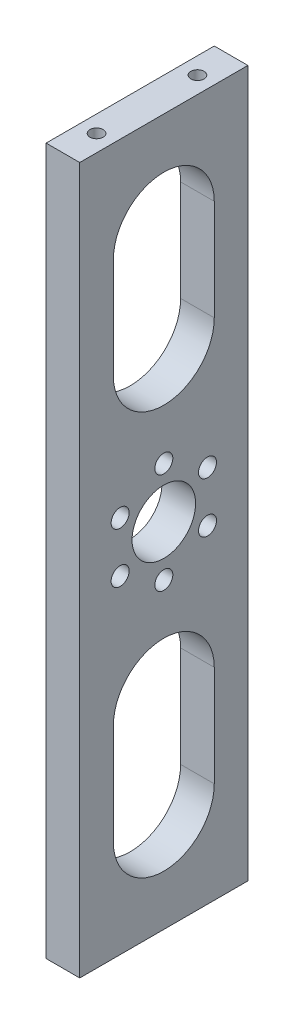
SolidWorks part; units mm, degrees
material "6061 Alloy"
ref_plane "Front Plane" through (0, 0, 0) normal (0, 0, 1) x (1, 0, 0)
ref_plane "Top Plane" through (0, 0, 0) normal (0, 1, 0) x (1, 0, 0)
ref_plane "Right Plane" through (0, 0, 0) normal (1, 0, 0) x (0, 0, -1)
sketch "Sketch1" plane through (0, 0, 0) normal (1, 0, 0) x (0, 0, -1)
  line L1 (-15.875, -66.675) -> (15.875, -66.675)
  line L2 (-15.875, -66.675) -> (-15.875, 66.675)
  line L3 (-15.875, 66.675) -> (15.875, 66.675)
  line L4 (15.875, -66.675) -> (15.875, 66.675)
  line L5 (-15.875, -66.675) -> (15.875, 66.675) construction
  line L6 (-15.875, 66.675) -> (15.875, -66.675) construction
  point P0 (0, 0)
  dimension "D1" = 31.75
  dimension "D2" = 133.35
extrude "Boss-Extrude1" add sketch "Sketch1" along normal mid plane 6.35
sketch "Sketch2" plane through (0, 66.675, 0) normal (0, 1, 0) x (1, 0, 0)
  line L0 (0, 9.525) -> (0, -9.525) construction
  line L1 (-3.175, 15.875) -> (-3.175, -15.875) construction
  line L2 (3.175, 15.875) -> (-3.175, 15.875) construction
  point P2 (0, 0)
  point P5 (-3.175, 0)
  point P8 (0, 15.875)
  point P10 (0, 9.525)
  point P11 (0, -9.525)
  dimension "D1" = 19.05
hole_wizard "M3x0.5 Tapped Hole1" positions "Sketch3" profile "Sketch5" tap size "M3x0.5" standard "ANSI Metric"
sketch "Sketch3" plane through (0, 66.675, 0) normal (0, 1, 0) x (1, 0, 0)
  point P0 (0, 9.525)
  point P3 (0, -9.525)
sketch "Sketch5" plane through (0, 66.675, -9.525) normal (1, 0, 0) x (0, 0, 1)
  line L0 (0, 0) -> (0, 13.4511)
  line L1 (0, 13.4511) -> (1.25, 12.7)
  line L2 (1.25, 12.7) -> (1.25, 0)
  line L5 (1.25, 0) -> (0, 0)
  line L10 (0, 13.4511) -> (-1.25, 12.7) construction
  line L11 (0, -6.35) -> (0, 107.95) construction
  dimension "Tap Drill Dia." = 2.5
  dimension "Tap Drill Depth" = 12.7
  dimension "Drill Angle" = 118
cosmetic thread "Hole Thread1" parameters "D1"=6.096, "D2"=3
cosmetic thread "Hole Thread2" parameters "D1"=6.096, "D2"=3
mirror "Mirror1" about plane through (0, 0, 0) normal (0, 1, 0) of "M3x0.5 Tapped Hole1"
cosmetic thread "Hole Thread3" parameters "D1"=6.096, "D2"=3
cosmetic thread "Hole Thread4" parameters "D1"=6.096, "D2"=3
sketch "Sketch6" plane through (-3.175, 0, 0) normal (-1, 0, 0) x (0, 0, 1)
  point P0 (0, 0)
hole_wizard "Ø12.0mm Dowel Hole1" positions "Sketch7" profile "Sketch8" hole size "Ø12.0" standard "ANSI Metric" end condition through all
sketch "Sketch7" plane through (-3.175, 0, 0) normal (-1, 0, 0) x (0, 0, 1)
  point P0 (0, 0)
sketch "Sketch8" plane through (-3.175, 0, 0) normal (0, 1, 0) x (0, 0, 1)
  line L0 (0, 0) -> (0, 6.35)
  line L1 (0, 6.35) -> (6, 6.35)
  line L2 (6, 6.35) -> (6, 0)
  line L5 (6, 0) -> (0, 0)
  line L11 (0, -6.35) -> (0, 107.95) construction
  dimension "Thru Hole Dia." = 12
  dimension "Thru Hole Depth" = 6.35
sketch "Sketch9" plane through (-3.175, 0, 0) normal (-1, 0, 0) x (0, 0, 1)
  point P0 (0, 9.525)
  point P1 (8.2489, 4.7625)
  point P3 (8.2489, -4.7625)
  point P5 (0, -9.525)
  point P7 (-8.2489, -4.7625)
  point P9 (-8.2489, 4.7625)
hole_wizard "CBORE for M3 SHCS1" positions "Sketch10" profile "Sketch11" counterbore size "M3" standard "ANSI Metric"
sketch "Sketch10" plane through (-3.175, 0, 0) normal (-1, 0, 0) x (0, 0, 1)
  point P0 (8.2489, -4.7625)
  point P3 (8.2489, 4.7625)
  point P6 (0, 9.525)
  point P9 (-8.2489, 4.7625)
  point P12 (-8.2489, -4.7625)
  point P15 (0, -9.525)
sketch "Sketch11" plane through (-3.175, -4.7625, 8.2489) normal (0, 1, 0) x (0, 0, 1)
  line L0 (0, 0) -> (0, 12.7)
  line L1 (0, 12.7) -> (1.7, 11.6785)
  line L2 (1.7, 11.6785) -> (1.7, 2)
  line L3 (1.7, 2) -> (2.25, 2)
  line L4 (2.25, 2) -> (2.25, 0)
  line L5 (2.25, 0) -> (0, 0)
  line L10 (0, 12.7) -> (-1.7, 11.6785) construction
  line L11 (0, -6.35) -> (0, 107.95) construction
  dimension "Hole Dia." = 3.4
  dimension "Hole Depth" = 12.7
  dimension "C'Bore Dia." = 4.5
  dimension "C'Bore Depth" = 2
  dimension "Drill Angle" = 118
sketch "Sketch12" plane through (3.175, 0, 0) normal (1, 0, 0) x (0, 0, -1)
  line L0 (0, 47.625) -> (0, 28.575) construction
  line L1 (9.525, 47.625) -> (9.525, 28.575)
  line L2 (-9.525, 47.625) -> (-9.525, 28.575)
  line L3 (0, -28.575) -> (0, -47.625) construction
  line L4 (9.525, -28.575) -> (9.525, -47.625)
  line L5 (-9.525, -28.575) -> (-9.525, -47.625)
  line L6 (0, 38.1) -> (0, -38.1) construction
  line L7 (3.4925, 0) -> (-3.4925, 0) construction
  arc A0 (9.525, 47.625) -> (-9.525, 47.625) centre (0, 47.625) ccw
  arc A1 (-9.525, 28.575) -> (9.525, 28.575) centre (0, 28.575) ccw
  arc A2 (9.525, -28.575) -> (-9.525, -28.575) centre (0, -28.575) ccw
  arc A3 (-9.525, -47.625) -> (9.525, -47.625) centre (0, -47.625) ccw
  point P3 (0, 38.1)
  point P8 (0, -38.1)
  point P20 (0, 0)
  dimension "D1" = 19.05
  dimension "D2" = 76.2
  dimension "D3" = 19.05
extrude "Cut-Extrude1" cut sketch "Sketch12" against normal through all contours L5 A3 L4 A2 | L1 A1 L2 A0
